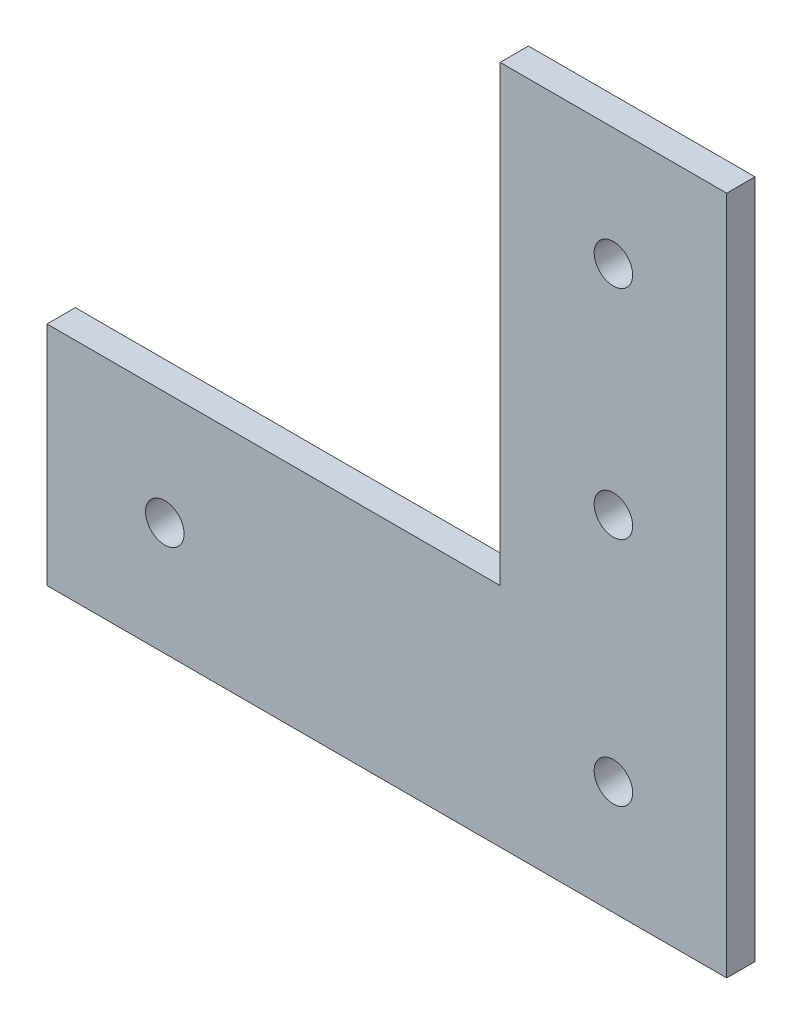
SolidWorks part; units mm, degrees
ref_plane "Front Plane" through (0, 0, 0) normal (0, 0, 1) x (1, 0, 0)
ref_plane "Top Plane" through (0, 0, 0) normal (0, 1, 0) x (1, 0, 0)
ref_plane "Right Plane" through (0, 0, 0) normal (1, 0, 0) x (0, 0, -1)
sketch "Sketch1" plane through (0, 0, 0) normal (0, 0, 1) x (1, 0, 0)
  line L1 (-38.1, -38.1) -> (38.1, -38.1)
  line L2 (-38.1, -38.1) -> (-38.1, 38.1)
  line L3 (-38.1, 38.1) -> (38.1, 38.1)
  line L4 (38.1, -38.1) -> (38.1, 38.1)
  line L5 (-38.1, -38.1) -> (38.1, 38.1) construction
  line L6 (-38.1, 38.1) -> (38.1, -38.1) construction
  point P0 (0, 0)
  dimension "D1" = 76.2
  dimension "D2" = 76.2
extrude "Boss-Extrude1" add sketch "Sketch1" along normal blind 3.175
sketch "Sketch2" plane through (0, 0, 0) normal (0, 0, -1) x (-1, 0, 0)
  line L1 (38.1, 38.1) -> (-12.7, 38.1)
  line L2 (38.1, 38.1) -> (38.1, -12.7)
  line L3 (38.1, -12.7) -> (-12.7, -12.7)
  line L4 (-12.7, 38.1) -> (-12.7, -12.7)
  dimension "D1" = 50.8
  dimension "D2" = 50.8
extrude "Cut-Extrude1" cut sketch "Sketch2" against normal blind 6.35
sketch "Sketch3" plane through (0, 0, 0) normal (0, 0, -1) x (-1, 0, 0)
  line L0 (-12.7, -12.7) -> (-38.1, -38.1) construction
  circle A0 centre (-25.4, -25.4) radius 2.159
  dimension "D1" = 4.318
extrude "Cut-Extrude2" cut sketch "Sketch3" against normal blind 6.35
ref_plane "Plane1" through (-38.1, -38.1, 0) normal (0, -1, 0) x (-1, 0, 0)
sketch "Sketch5" plane through (0, 0, 0) normal (0, 0, -1) x (-1, 0, 0)
  line L0 (38.1, -25.4) -> (-38.1, -25.4) construction
  line L1 (38.1, -12.7) -> (38.1, -38.1) construction
  line L2 (-38.1, -38.1) -> (-38.1, 38.1) construction
  circle A0 centre (24.892, -25.4) radius 2.159
  dimension "D1" = 4.318
  dimension "D2" = 13.208
extrude "Cut-Extrude3" cut sketch "Sketch5" against normal blind 6.35
sketch "Sketch6" plane through (0, 0, 3.175) normal (0, 0, 1) x (1, 0, 0)
  line L0 (12.7, -12.7) -> (38.1, -12.7) construction
  line L1 (38.1, -38.1) -> (38.1, 38.1) construction
  line L2 (25.4, -12.7) -> (25.4, 38.1) construction
  line L3 (38.1, 38.1) -> (12.7, 38.1) construction
  circle A0 centre (25.4, 0.508) radius 2.159
  circle A1 centre (25.4, 24.892) radius 2.159
  dimension "D1" = 13.208
  dimension "D3" = 4.318
  dimension "D4" = 4.318
  dimension "D2" = 13.208
extrude "Cut-Extrude4" cut sketch "Sketch6" against normal through all
